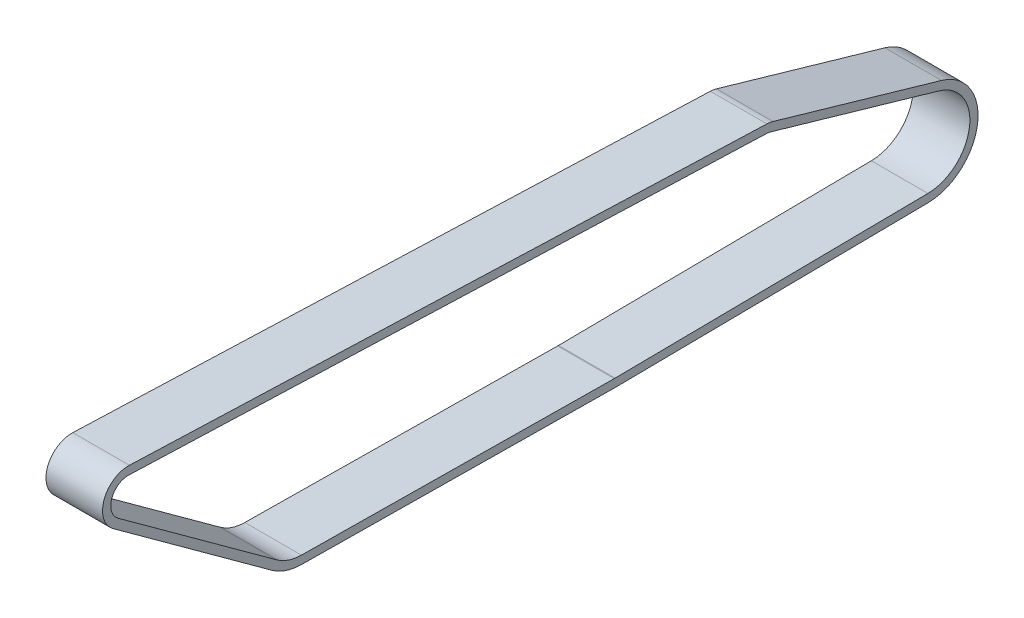
SolidWorks part; units mm, degrees
ref_plane "Front Plane" through (0, 0, 0) normal (0, 0, 1) x (1, 0, 0)
ref_plane "Top Plane" through (0, 0, 0) normal (0, 1, 0) x (1, 0, 0)
ref_plane "Right Plane" through (0, 0, 0) normal (1, 0, 0) x (0, 0, -1)
sketch "Sketch1" plane through (0, 0, 0) normal (1, 0, 0) x (0, 0, -1)
  line L4 (19.6252, 155.6463) -> (592.1981, 134.8848) construction
  line L5 (595.8764, 134.2959) -> (747.1764, 90.5776) construction
  line L6 (19.6252, 155.6463) -> (592.1981, 134.8848)
  line L7 (595.8764, 134.2959) -> (747.1764, 90.5776)
  line L10 (9.7122, 126.9434) -> (152.3966, 23.1632) construction
  line L11 (9.7122, 126.9434) -> (152.3966, 23.1632)
  line L13 (174.3767, 15.8774) -> (455.2731, 12.7024) construction
  line L14 (456.1343, 12.7024) -> (737.0306, 15.8774) construction
  line L15 (174.3767, 15.8774) -> (455.2731, 12.7024)
  line L16 (456.1343, 12.7024) -> (737.0306, 15.8774)
  arc A4 (595.8764, 134.2959) -> (592.1981, 134.8848) centre (591.6458, 119.6548) ccw construction
  arc A5 (595.8764, 134.2959) -> (592.1981, 134.8848) centre (591.6458, 119.6548) ccw
  circle A6 centre (19.05, 139.7817) radius 15.875 construction
  arc A7 (19.6252, 155.6463) -> (9.7122, 126.9434) centre (19.05, 139.7817) ccw
  arc A9 (455.2731, 12.7024) -> (456.1343, 12.7024) centre (455.7037, 50.8) ccw construction
  circle A11 centre (174.8073, 53.975) radius 38.1 construction
  arc A12 (455.2731, 12.7024) -> (456.1343, 12.7024) centre (455.7037, 50.8) ccw
  arc A13 (152.3966, 23.1632) -> (174.3767, 15.8774) centre (174.8073, 53.975) ccw
  circle A14 centre (736.6, 53.975) radius 38.1 construction
  arc A15 (737.0306, 15.8774) -> (747.1764, 90.5776) centre (736.6, 53.975) ccw
extrude "Extrude-Thin1" add sketch "Sketch1" along normal blind 50.8 thin thin type one direction wall 7.366
